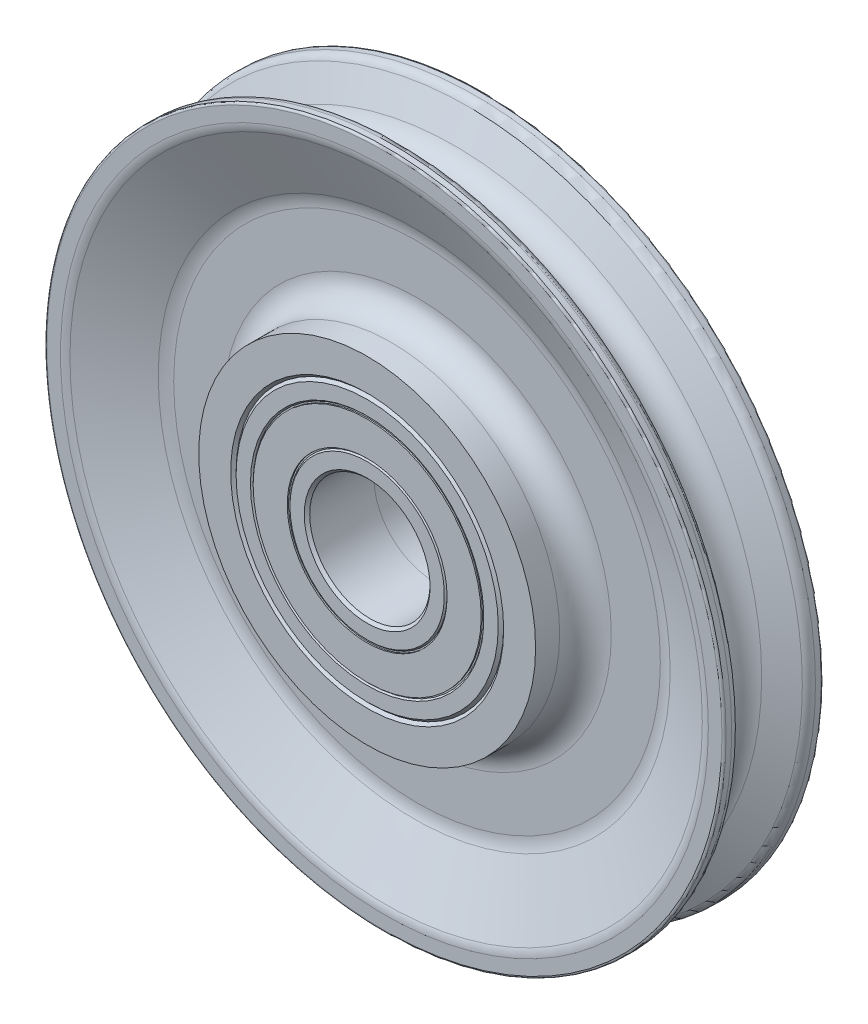
SolidWorks part; units mm, degrees
ref_plane "Front Plane" through (0, 0, 0) normal (0, 0, 1) x (1, 0, 0)
ref_plane "Top Plane" through (0, 0, 0) normal (0, 1, 0) x (1, 0, 0)
ref_plane "Right Plane" through (0, 0, 0) normal (1, 0, 0) x (0, 0, -1)
sketch "Sketch1" plane through (0, 0, 0) normal (0, 0, 1) x (1, 0, 0)
  line L0 (0, 0) -> (0, 127) construction
  circle A0 centre (0, 0) radius 127
  circle A1 centre (0, 0) radius 22.5
  circle A2 centre (0, 0) radius 109.728
  point P5 (0, 127)
  point P6 (0, 109.728)
  point P7 (0, 22.5)
  dimension "OD" = 254
  dimension "For Shaft Diameter" = 45
  dimension "Pulley Diameter" = 219.456
sketch "Sketch2" plane through (0, 0, 0) normal (1, 0, 0) x (0, 0, -1)
  line L0 (-24.9936, 0) -> (24.9936, 0) construction
  line L1 (-24.9936, 0) -> (-24.9936, 22.5)
  line L2 (-24.9936, 22.5) -> (24.9936, 22.5) construction
  line L3 (24.9936, 22.5) -> (24.9936, 0)
  line L4 (-24.9936, 22.5) -> (-24.9936, 50.038)
  line L5 (-24.9936, 50.038) -> (24.9936, 50.038)
  line L6 (24.9936, 50.038) -> (24.9936, 22.5)
  line L7 (-24.9936, 50.038) -> (-24.9936, 62.992)
  line L8 (-24.9936, 62.992) -> (-6.35, 62.992)
  line L9 (-6.35, 62.992) -> (-6.35, 93.472)
  line L11 (0, 127) -> (0, 0) construction
  line L12 (-24.9936, 49.022) -> (-23.9776, 50.038)
  line L13 (-7.8269, 114.7143) -> (-12.6668, 125.0935)
  line L14 (-6.35, 93.472) -> (-18.542, 119.6178)
  line L16 (-18.542, 119.6178) -> (-18.542, 127)
  line L17 (-18.542, 127) -> (-15.6594, 127)
  arc A0 (0, 109.728) -> (-7.8269, 114.7143) centre (0, 118.364) cw
  arc A1 (-12.6668, 125.0935) -> (-15.6594, 127) centre (-15.6594, 123.698) ccw
  circle A2 centre (0, 117.6655) radius 7.9375 construction
  arc A3 (-16.002, 62.992) -> (-6.35, 72.644) centre (-16.002, 72.644) ccw
  circle A5 centre (0, -117.6655) radius 7.9375 construction
  arc A6 (-7.3971, 95.7175) -> (-6.35, 90.9943) centre (-17.526, 90.9943) cw
  arc A7 (-18.542, 121.1382) -> (-17.8995, 118.2399) centre (-11.684, 121.1382) ccw
  arc A8 (-18.542, 126.238) -> (-17.78, 127) centre (-17.78, 126.238) cw
  point P31 (0, -109.728)
  point P32 (0, 109.728)
  dimension "D8" = 3.302
  dimension "D9" = 8.636
  dimension "For Rope Diameter" = 15.875
  dimension "D11" = 9.652
  dimension "D14" = 11.176
  dimension "D15" = 0.762
  dimension "D16" = 6.858
  dimension "Width" = 49.9872
  dimension "D2" = 50.038
  dimension "D4" = 62.992
  dimension "D5" = 45
  dimension "D6" = 1.016
  dimension "D7" = 25
  dimension "D3" = 6.35
  dimension "D10" = 25
  dimension "D13" = 37.084
  dimension "D12" = 30.48
sketch "Sketch3" plane through (0, 0, 0) normal (1, 0, 0) x (0, 0, -1)
  line L0 (-24.9936, 22.5) -> (-24.9936, 29.3845) construction
  line L1 (-24.9936, 22.5) -> (-24.9936, 50.038) construction
  line L2 (-24.9936, 50.038) -> (-24.9936, 43.1535) construction
  line L4 (-24.9936, 43.1535) -> (-22.9616, 43.1535)
  line L5 (-24.9936, 43.1535) -> (-24.9936, 29.3845)
  line L6 (-24.9936, 29.3845) -> (-22.9616, 29.3845)
  line L7 (-22.9616, 43.1535) -> (-22.9616, 29.3845)
  dimension "D1" = 2.032
  dimension "D2" = 13.769
sketch "Sketch4" plane through (0, 0, 0) normal (1, 0, 0) x (0, 0, -1)
  line L0 (-24.9936, 22.5) -> (0, 22.5)
  line L1 (0, 22.5) -> (0, 50.038)
  line L2 (0, 109.728) -> (0, -109.728) construction
  line L3 (0, 50.038) -> (-23.9776, 50.038)
  line L4 (-23.9776, 50.038) -> (-24.9936, 49.022)
  line L5 (-24.9936, 49.022) -> (-24.9936, 43.1535)
  line L6 (-24.9936, 43.1535) -> (-22.9616, 43.1535)
  line L7 (-22.9616, 43.1535) -> (-22.9616, 29.3845)
  line L8 (-22.9616, 29.3845) -> (-24.9936, 29.3845)
  line L9 (-24.9936, 29.3845) -> (-24.9936, 22.5)
  line L10 (-24.9936, 0) -> (24.9936, 0) construction
  line L11 (-24.9936, 0) -> (24.9936, 0) construction
revolve "Revolve1" add sketch "Sketch4" angle 360 about L11
chamfer "Chamfer1" distance 0.508 angle 45 2 edges at (43.1535, 0, 24.9936) (29.3845, 0, 24.9936)
sketch "Sketch5" plane through (0, 0, 0) normal (1, 0, 0) x (0, 0, -1)
  line L0 (-24.9936, 43.1535) -> (-24.9936, 29.3845) construction
  line L1 (-24.9936, 29.3845) -> (-22.9616, 29.3845) construction
  line L2 (-22.9616, 43.1535) -> (-22.9616, 29.3845) construction
  line L3 (-24.9936, 43.1535) -> (-22.9616, 43.1535) construction
  line L4 (-24.9936, 43.1535) -> (-24.9936, 29.3845)
  line L5 (-24.9936, 29.3845) -> (-22.9616, 29.3845)
  line L6 (-22.9616, 43.1535) -> (-22.9616, 29.3845)
  line L7 (-24.9936, 43.1535) -> (-22.9616, 43.1535)
  line L8 (-24.9936, 0) -> (24.9936, 0) construction
  line L9 (-24.9936, 0) -> (24.9936, 0) construction
revolve "Revolve2" add sketch "Sketch5" angle 360 about L9
sketch "Sketch7" plane through (0, 0, 24.9936) normal (0, 0, 1) x (1, 0, 0)
  circle A0 centre (0, 0) radius 43.1535 construction
  circle A1 centre (0, 0) radius 43.1535
  circle A2 centre (0, 0) radius 42.6455
  circle A3 centre (0, 0) radius 29.3845 construction
  circle A4 centre (0, 0) radius 29.3845
  circle A5 centre (0, 0) radius 29.8925
  circle M1 centre (0, 0) radius 29.3845
  circle M2 centre (0, 0) radius 43.1535
  dimension "D1" = 0.508
  dimension "D2" = 0.508
extrude "Cut-Extrude1" cut sketch "Sketch7" against normal blind 0.508 contours A5 M1 | A2 M2
chamfer "Chamfer4" distance 1.016 angle 45 1 edges at (22.5, 0, 24.9936)
mirror "Mirror1" about plane through (0, 0, 0) normal (0, 0, 1) of bodies 110 104 105
sketch "Sketch6" plane through (0, 0, 0) normal (1, 0, 0) x (0, 0, -1)
  line L0 (-23.9776, 50.038) -> (-24.9936, 51.054)
  line L1 (-24.9936, 50.038) -> (-24.9936, 62.992) construction
  line L2 (-24.9936, 49.022) -> (-23.9776, 50.038) construction
  line L3 (-24.9936, 51.054) -> (-24.9936, 62.992)
  line L4 (-24.9936, 62.992) -> (-16.002, 62.992)
  line L6 (-7.8269, 114.7143) -> (-12.6668, 125.0935) construction
  line L7 (-7.8269, 114.7143) -> (-12.6668, 125.0935)
  line L9 (0, 109.728) -> (0, 50.038)
  line L10 (0, 109.728) -> (0, -109.728) construction
  line L11 (0, 50.038) -> (-23.9776, 50.038)
  line L12 (-24.9936, 0) -> (24.9936, 0) construction
  line L13 (-24.9936, 0) -> (24.9936, 0) construction
  line L14 (-15.6594, 127) -> (-17.78, 127)
  line L15 (-18.542, 126.238) -> (-18.542, 121.1382)
  line L16 (-17.8995, 118.2399) -> (-7.3971, 95.7175)
  line L17 (-6.35, 90.9943) -> (-6.35, 72.644)
  arc A0 (-16.002, 62.992) -> (-6.35, 72.644) centre (-16.002, 72.644) ccw construction
  arc A1 (-16.002, 62.992) -> (-6.35, 72.644) centre (-16.002, 72.644) ccw
  arc A2 (-7.8269, 114.7143) -> (0, 109.728) centre (0, 118.364) ccw construction
  arc A3 (-12.6668, 125.0935) -> (-15.6594, 127) centre (-15.6594, 123.698) ccw construction
  arc A5 (-7.8269, 114.7143) -> (0, 109.728) centre (0, 118.364) ccw
  arc A6 (-12.6668, 125.0935) -> (-15.6594, 127) centre (-15.6594, 123.698) ccw
  arc A8 (-18.542, 121.1382) -> (-17.8995, 118.2399) centre (-11.684, 121.1382) ccw construction
  arc A9 (-6.35, 90.9943) -> (-7.3971, 95.7175) centre (-17.526, 90.9943) ccw construction
  arc A10 (-18.542, 121.1382) -> (-17.8995, 118.2399) centre (-11.684, 121.1382) ccw
  arc A11 (-6.35, 90.9943) -> (-7.3971, 95.7175) centre (-17.526, 90.9943) ccw
  arc A12 (-17.78, 127) -> (-18.542, 126.238) centre (-17.78, 126.238) ccw construction
  arc A13 (-17.78, 127) -> (-18.542, 126.238) centre (-17.78, 126.238) ccw
revolve "Revolve3" add sketch "Sketch6" angle 360 about L13
mirror "Mirror2" about plane through (0, 109.728, 0) normal (0, 0, 1) of bodies 108
equation "\"D1@Sketch3\"=2*\"D6@Sketch2\""
equation "\"D2@Sketch3\"=(\"D2@Sketch2\"-(0.5*\"For Shaft Diameter@Sketch1\"))/2"
equation "\"D1@Chamfer1\"=0.5*\"D6@Sketch2\""
equation "\"D1@Chamfer4\"=\"D6@Sketch2\""
equation "\"D1@Sketch7\"=\"D6@Sketch2\"*0.5"
equation "\"D1@Cut-Extrude1\"=\"D1@Chamfer1\""
equation "\"D2@Sketch7\"=\"D1@Sketch7\""
